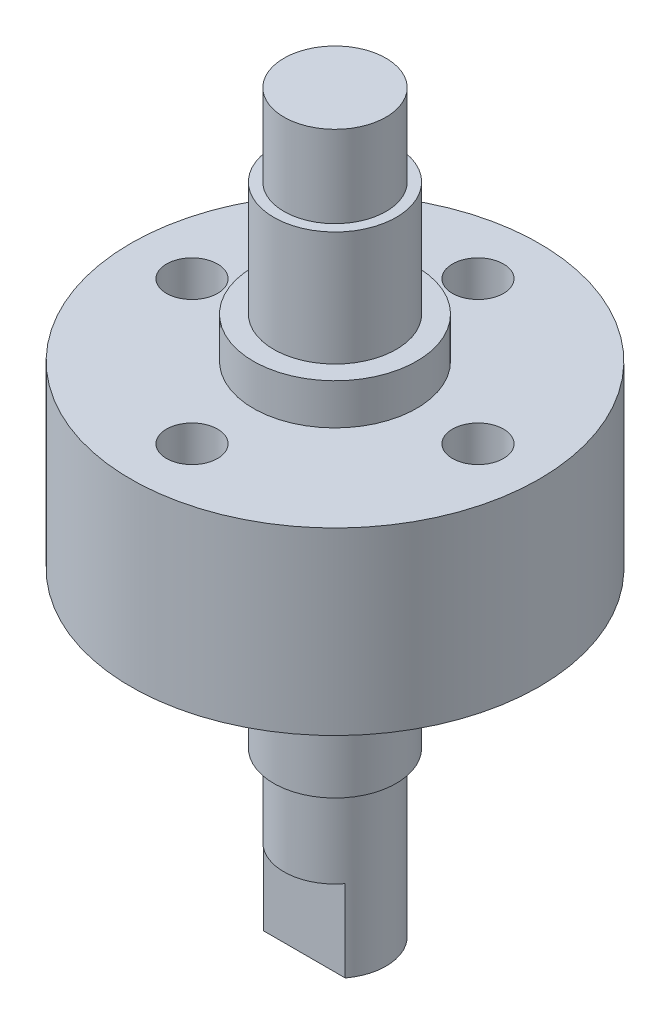
SolidWorks part; units mm, degrees
ref_plane "前视基准面" through (0, 0, 0) normal (0, 0, 1) x (1, 0, 0)
ref_plane "上视基准面" through (0, 0, 0) normal (0, 1, 0) x (1, 0, 0)
ref_plane "右视基准面" through (0, 0, 0) normal (1, 0, 0) x (0, 0, -1)
sketch "Model" plane through (0, 0, 0) normal (0, 0, 1) x (1, 0, 0)
  line L0 (-1.7864, 30.378) -> (-1.7864, -5.622)
  line L1 (8.2136, 9.978) -> (8.2136, 18.778)
  line L3 (2.2136, 18.778) -> (2.2136, 20.778)
  line L5 (2.2136, 7.978) -> (2.2136, 9.978)
  line L7 (1.2136, 2.378) -> (1.2136, 7.978)
  line L9 (1.2136, 20.778) -> (1.2136, 26.378)
  line L11 (0.7136, -5.622) -> (0.7136, 2.378)
  line L13 (0.7136, 26.378) -> (0.7136, 30.378)
  line L16 (1.2136, 20.778) -> (2.2136, 20.778)
  line L20 (-1.7864, -5.622) -> (0.7136, -5.622)
  line L21 (-1.7864, 30.378) -> (0.7136, 30.378)
  line L22 (-1.7864, 30.378) -> (-1.7864, -5.622) construction
  line L23 (0.7136, 26.378) -> (1.2136, 26.378)
  line L24 (2.2136, 18.778) -> (8.2136, 18.778)
  line L25 (2.2136, 9.978) -> (8.2136, 9.978)
  line L26 (1.2136, 7.978) -> (2.2136, 7.978)
  line L27 (0.7136, 2.378) -> (1.2136, 2.378)
  dimension "D1" = 4
  dimension "D2" = 5.6
  dimension "D3" = 2
  dimension "D4" = 8.8
  dimension "D5" = 2
  dimension "D6" = 5.6
  dimension "D7" = 8
  dimension "D8" = 2.5
  dimension "D9" = 3
  dimension "D10" = 4
  dimension "D11" = 10
  dimension "D12" = 4
  dimension "D13" = 3
  dimension "D14" = 2.5
revolve "旋转1" add sketch "Model" angle 360 about L22
sketch "草图2" plane through (0, 9.978, 0) normal (0, -1, 0) x (1, 0, 0)
  circle A0 centre (-1.7864, 0) radius 7 construction
  circle A1 centre (-1.7864, 7) radius 1.5
  dimension "D1" = 14
  dimension "D2" = 3
hole_wizard "M3 螺纹孔1" positions "3D草图1" profile "草图4" tap size "M3" standard "GB"
sketch3d "3D草图1"
  point P0 (-1.7864, 9.978, 7)
sketch "草图4" plane through (-1.7864, 9.978, 7) normal (1, 0, 0) x (0, 0, -1)
  line L0 (0, 0) -> (0, 20.4)
  line L1 (0, 20.4) -> (1.25, 20.4)
  line L2 (1.25, 20.4) -> (1.25, 0)
  line L5 (1.25, 0) -> (0, 0)
  line L11 (0, -6.35) -> (0, 107.95) construction
  dimension "通孔螺纹孔钻头直径" = 2.5
  dimension "通孔螺纹孔钻头深度" = 20.4
cosmetic thread "孔螺蚊线1" parameters "D2"=3
pattern_circular "阵列(圆周)1" count 4 over 360 of "M3 螺纹孔1"
sketch "草图5" plane through (0, -5.622, 0) normal (0, -1, 0) x (1, 0, 0)
  line L0 (-3.7864, 1.5) -> (0.2136, 1.5)
  line L1 (0.2136, 1.5) -> (0.2136, 5.3333)
  line L2 (0.2136, 5.3333) -> (-4.133, 4.4308)
  line L3 (-4.133, 4.4308) -> (-3.7864, 1.5)
  circle A0 centre (-1.7864, 0) radius 2.5 construction
  dimension "D1" = 1.5
extrude "切除-拉伸1" cut sketch "草图5" against normal blind 4
